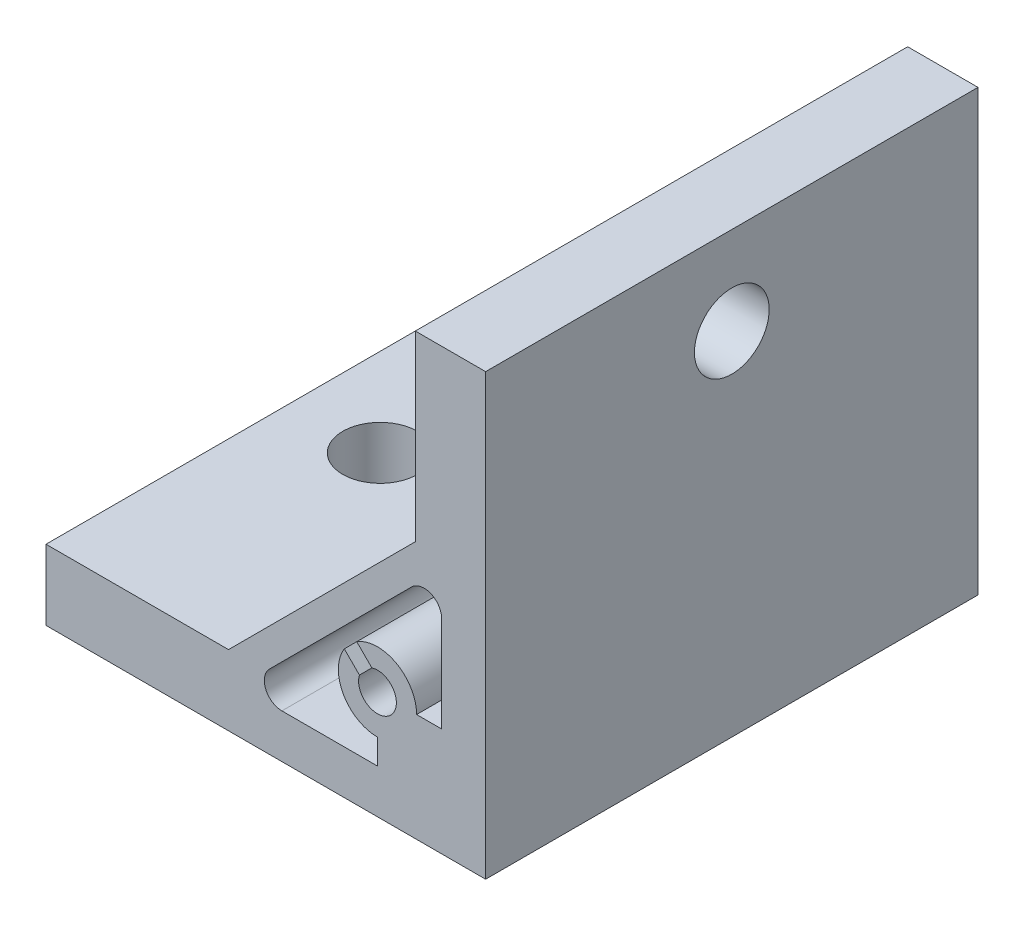
SolidWorks part; units mm, degrees
ref_plane "前视基准面" through (0, 0, 0) normal (0, 0, 1) x (1, 0, 0)
ref_plane "上视基准面" through (0, 0, 0) normal (0, 1, 0) x (1, 0, 0)
ref_plane "右视基准面" through (0, 0, 0) normal (1, 0, 0) x (0, 0, -1)
sketch "草图1" plane through (0, 0, 0) normal (0, 0, 1) x (1, 0, 0)
  line B0 (0, 0) -> (50, 0)
  line B1 (50, 0) -> (50, 50)
  line B2 (0, 8) -> (20.7574, 8)
  line B3 (42, 29.2426) -> (42, 50)
  line B4 (0, 8) -> (0, 0)
  line B5 (42, 50) -> (50, 50)
  line B6 (37.0613, 14.3529) -> (35.341, 16.0733)
  line B7 (35.6471, 12.9387) -> (33.9267, 14.659)
  line B8 (25.4142, 8.4142) -> (41.5858, 24.5858)
  line B9 (20.7574, 8) -> (42, 29.2426)
  line B10 (26.8284, 5) -> (37.7, 5)
  line B11 (45, 23.1716) -> (45, 12.3)
  line B12 (37.7, 5) -> (37.7, 7.85)
  line B13 (42.15, 12.3) -> (45, 12.3)
  arc B14 (33.9267, 14.659) -> (37.7, 7.85) centre (37.7, 12.3) ccw
  arc B15 (42.15, 12.3) -> (35.341, 16.0733) centre (37.7, 12.3) ccw
  arc B16 (35.6471, 12.9387) -> (37.0613, 14.3529) centre (37.7, 12.3) ccw
  arc B17 (25.4142, 8.4142) -> (26.8284, 5) centre (26.8284, 7) ccw
  arc B18 (45, 23.1716) -> (41.5858, 24.5858) centre (43, 23.1716) ccw
sketch_block_instance "A$C19004297-1"
sketch_block "A$C19004297"
extrude "凸台-拉伸1" add sketch "草图1" along normal mid plane 56
sketch "草图3" plane through (0, 8, 0) normal (0, 1, 0) x (1, 0, 0)
  line L0 (0, -28) -> (0, 28) construction
  circle A0 centre (10, 0) radius 4.25
  dimension "D1" = 10
extrude "切除-拉伸1" cut sketch "草图3" against normal through all
sketch "草图4" plane through (6.3787, -6.3787, 0) normal (-0.7071, 0.7071, 0) x (0, 0, 1)
  line L0 (28, 35.3553) -> (-28, 35.3553) construction
  line L1 (28, 50.3762) -> (28, 20.3345) construction
  line L2 (-28, 50.3762) -> (-28, 20.3345) construction
ref_plane "基准面2" through (25, 25, 0) normal (-0.7071, -0.7071, 0) x (0, 0, 1)
mirror "镜向1" about plane through (25, 25, 0) normal (-0.7071, -0.7071, 0) of "切除-拉伸1"
